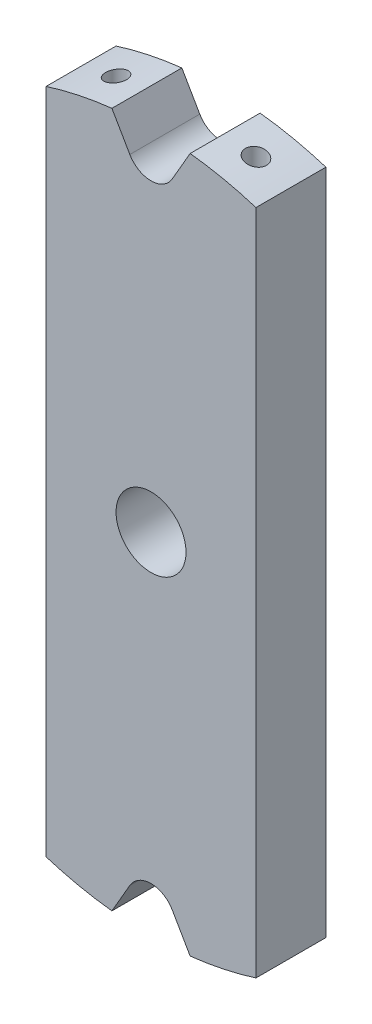
SolidWorks part; units mm, degrees
ref_plane "前视基准面" through (0, 0, 0) normal (0, 0, 1) x (1, 0, 0)
ref_plane "上视基准面" through (0, 0, 0) normal (0, 1, 0) x (1, 0, 0)
ref_plane "右视基准面" through (0, 0, 0) normal (1, 0, 0) x (0, 0, -1)
sketch "草图1" plane through (0, 0, 0) normal (0, 0, 1) x (1, 0, 0)
  line L0 (0, 0) -> (0, 27.9405) construction
  line L1 (-15, 47.697) -> (-15, -47.697)
  line L2 (15, 47.697) -> (15, -47.697)
  line L3 (3.0311, 45.25) -> (5.5924, 49.6863)
  line L4 (-3.0311, 45.25) -> (-5.5924, 49.6863)
  line L5 (0, 0) -> (77.5321, 0) construction
  line L6 (-3.0311, -45.25) -> (-5.5924, -49.6863)
  line L7 (3.0311, -45.25) -> (5.5924, -49.6863)
  arc A0 (-15, -47.697) -> (15, -47.697) centre (0, 0) ccw
  arc A1 (15, 47.697) -> (-15, 47.697) centre (0, 0) ccw
  arc A3 (3.0311, 45.25) -> (-3.0311, 45.25) centre (0, 47) cw
  arc A4 (3.0311, -45.25) -> (-3.0311, -45.25) centre (0, -47) ccw
  dimension "D1" = 100
  dimension "D3" = 3.5
  dimension "D2" = 15
  dimension "D4" = 30
  dimension "D5" = 47
extrude "凸台-拉伸1" add sketch "草图1" along normal blind 10 contours A4 L7 A0 L2 A1 L3 A3 L4 L1 L6
sketch "草图2" plane through (0, 0, 0) normal (0, 1, 0) x (1, 0, 0)
  line L0 (0, -5) -> (15, -5) construction
  line L3 (15, -10) -> (15, 0) construction
  line L4 (15, -10) -> (15, 0) construction
  circle A0 centre (-10, -5) radius 1.5
  circle A1 centre (10, -5) radius 1.5
  point P3 (15, -5)
  point P9 (0, 0)
  point P12 (5.255, -2.4403)
  dimension "D1" = 3
  dimension "D2" = 10
  dimension "D3" = 10
extrude "切除-拉伸1" cut sketch "草图2" against normal through all both and the other way through all
sketch "草图3" plane through (0, 0, 10) normal (0, 0, 1) x (1, 0, 0)
  circle A0 centre (0, 0) radius 5
  dimension "D1" = 10
extrude "切除-拉伸2" cut sketch "草图3" against normal through all and the other way through all
